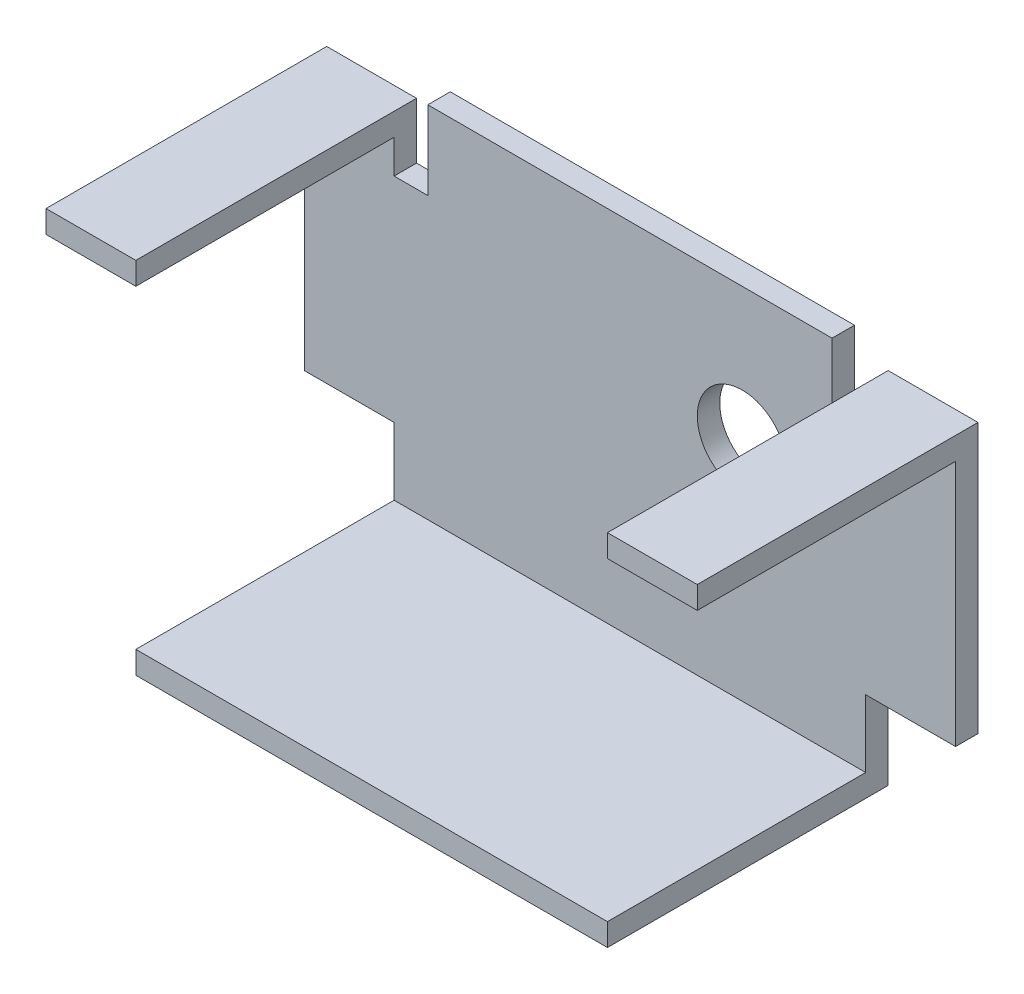
SolidWorks part; units mm, degrees
ref_plane "Front Plane" through (0, 0, 0) normal (0, 0, 1) x (1, 0, 0)
ref_plane "Top Plane" through (0, 0, 0) normal (0, 1, 0) x (1, 0, 0)
ref_plane "Right Plane" through (0, 0, 0) normal (1, 0, 0) x (0, 0, -1)
sketch "Sketch1" plane through (0, 0, 0) normal (0, 1, 0) x (1, 0, 0)
  line L0 (0, 0) -> (-42, 0)
  line L1 (-42, 0) -> (-42, 25)
  line L2 (-42, 25) -> (0, 25)
  line L3 (0, 25) -> (0, 0)
extrude "Boss-Extrude1" add sketch "Sketch1" along normal blind 2
sketch3d "3DSketch1"
  line L0 (0, 2, -25) -> (0, 8, -25)
  line L1 (0, 27, -25) -> (-3, 27, -25)
  line L2 (0, 8, -25) -> (8, 8, -25)
  line L3 (8, 8, -25) -> (8, 32, -25)
  line L4 (8, 32, -25) -> (0, 32, -25)
  line L5 (0, 32, -25) -> (0, 27, -25)
  line L6 (-3, 27, -25) -> (-3, 34, -25)
  line L7 (-3, 34, -25) -> (-39, 34, -25)
  line L8 (-3, 34, -25) -> (-11, 34, -25)
  line L9 (-42, 2, -25) -> (0, 2, -25)
  line L11 (-42, 2, -25) -> (-42, 8, -25)
  line L12 (-42, 8, -25) -> (-50, 8, -25)
  line L13 (-50, 8, -25) -> (-50, 31.9975, -25)
  line L14 (-50, 31.9975, -25) -> (-42, 32, -25)
  line L20 (-42, 32, -25) -> (-42, 27, -25)
  line L21 (-42, 27, -25) -> (-39, 27, -25)
  line L22 (-39, 27, -25) -> (-39, 34, -25)
extrude "Boss-Extrude2" add sketch "3DSketch1" along direction (0, 0, -1) on the side against the normal blind 2 contours L6 L1 L5 L4 L3 L2 L0 L9 L11 L12 L13 L14 L20 L21 L22 L7
sketch "Sketch2" plane through (0, 0, -23) normal (0, 0, 1) x (1, 0, 0)
  line L0 (-3, 34) -> (-11, 34)
  line L1 (-3, 34) -> (-39, 34) construction
  line L2 (-11, 34) -> (-11, 22)
  circle A0 centre (-11, 22) radius 4
extrude "Cut-Extrude1" cut sketch "Sketch2" against normal blind 2
sketch "Sketch3" plane through (0, 0, -23) normal (0, 0, 1) x (1, 0, 0)
  line L0 (-50, 31.9975) -> (-50, 29.9975)
  line L1 (-50, 8) -> (-50, 31.9975) construction
  line L2 (-50, 29.9975) -> (-42, 29.9975)
  line L3 (-42, 32) -> (-42, 27) construction
  line L4 (-42, 29.9975) -> (-42, 32)
  line L5 (-42, 32) -> (-50, 31.9975)
  line L6 (8, 32) -> (8, 30)
  line L7 (8, 8) -> (8, 32) construction
  line L8 (8, 30) -> (0, 30)
  line L9 (0, 32) -> (0, 27) construction
  line L10 (0, 30) -> (0, 32)
  line L11 (0, 32) -> (8, 32)
extrude "Boss-Extrude3" add sketch "Sketch3" along normal blind 23
